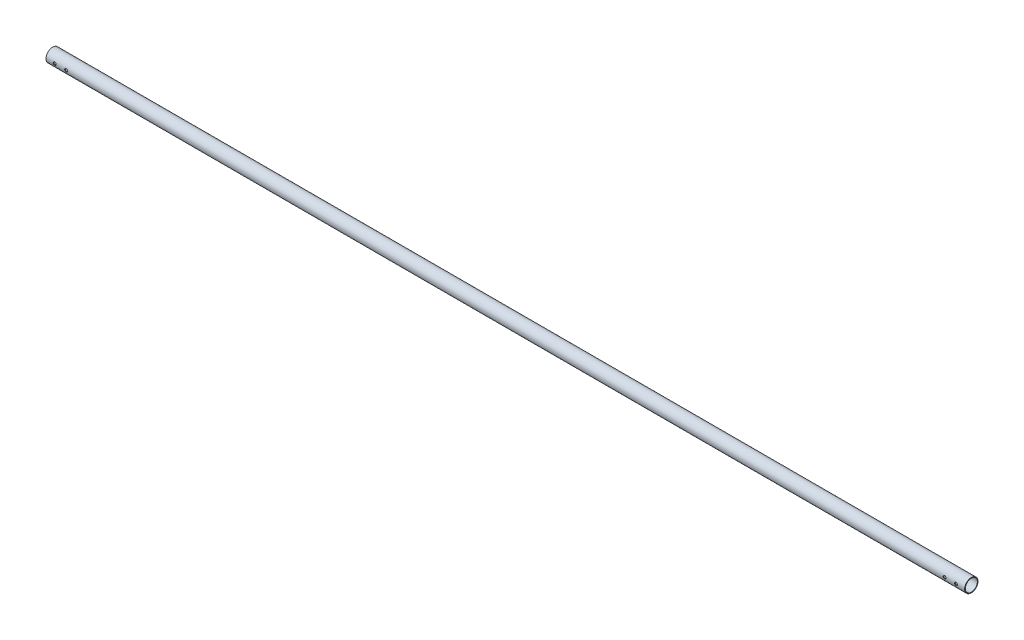
SolidWorks part; units mm, degrees
material "Galvanized Steel"
ref_plane "Front Plane" through (0, 0, 0) normal (0, 0, 1) x (1, 0, 0)
ref_plane "Top Plane" through (0, 0, 0) normal (0, 1, 0) x (1, 0, 0)
ref_plane "Right Plane" through (0, 0, 0) normal (1, 0, 0) x (0, 0, -1)
sketch "Sketch1" plane through (0, 0, 0) normal (1, 0, 0) x (0, 0, -1)
  circle A0 centre (0, 0) radius 14.7701
  circle A1 centre (0, 0) radius 13.3223
  dimension "D1" = 29.5402
  dimension "D2" = 26.6446
extrude "Boss-Extrude1" add sketch "Sketch1" along normal blind 2032
ref_plane "Plane1" through (1016, 0, 0) normal (1, 0, 0) x (0, 0, -1)
sketch "Sketch2" plane through (0, 0, 0) normal (0, 0, 1) x (1, 0, 0)
  line L0 (0, 14.7701) -> (0, -14.7701) construction
  circle A0 centre (19.05, 0) radius 3.175
  circle A1 centre (44.45, 0) radius 3.175
  point P4 (0, 0)
  dimension "D1" = 6.35
  dimension "D2" = 19.05
  dimension "D3" = 44.45
extrude "Cut-Extrude1" cut sketch "Sketch2" against normal through all both and the other way through all
mirror "Mirror1" about plane through (1016, 0, 0) normal (1, 0, 0) of "Cut-Extrude1"
